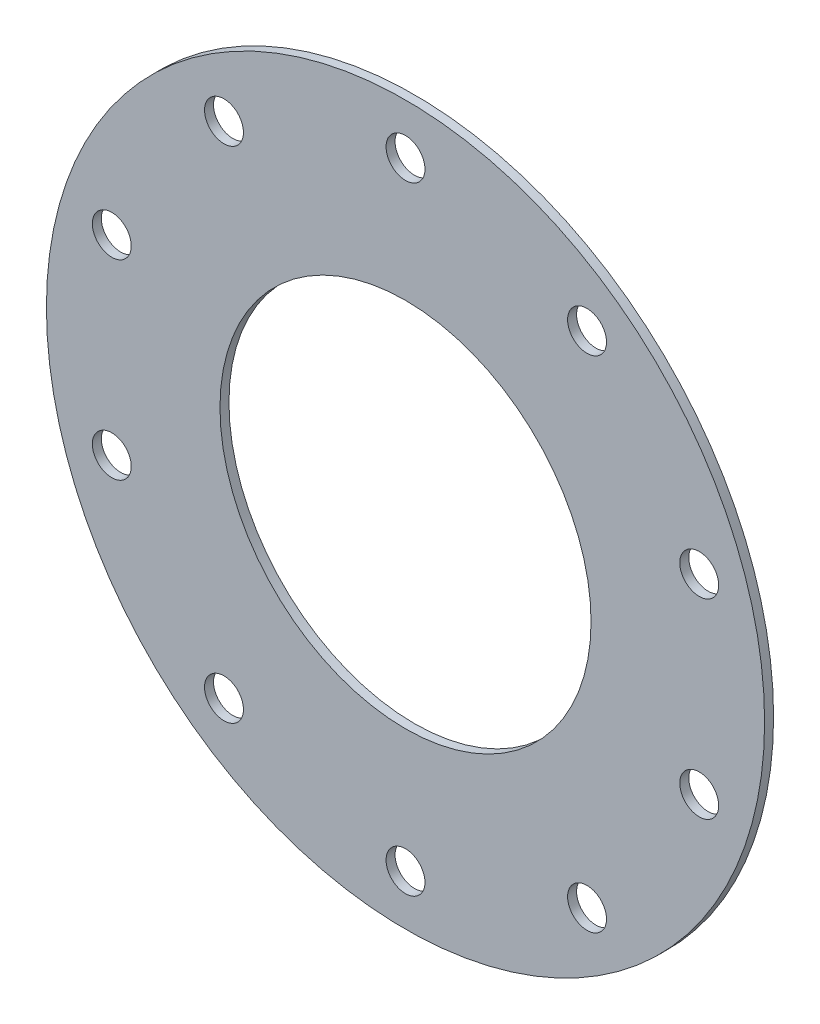
SolidWorks part; units mm, degrees
ref_plane "Front Plane" through (0, 0, 0) normal (0, 0, 1) x (1, 0, 0)
ref_plane "Top Plane" through (0, 0, 0) normal (0, 1, 0) x (1, 0, 0)
ref_plane "Right Plane" through (0, 0, 0) normal (1, 0, 0) x (0, 0, -1)
sketch "Sketch1" plane through (0, 0, 0) normal (0, 0, 1) x (1, 0, 0)
  circle A0 centre (0, 0) radius 60
  circle A1 centre (0, 0) radius 31
  circle A2 centre (0, 0) radius 51.6 construction
  circle A3 centre (0, 51.6) radius 3.25
  circle A4 centre (30.3297, 41.7453) radius 3.25
  circle A5 centre (49.0745, 15.9453) radius 3.25
  circle A6 centre (49.0745, -15.9453) radius 3.25
  circle A7 centre (30.3297, -41.7453) radius 3.25
  circle A8 centre (0, -51.6) radius 3.25
  circle A9 centre (-30.3297, -41.7453) radius 3.25
  circle A10 centre (-49.0745, -15.9453) radius 3.25
  circle A11 centre (-49.0745, 15.9453) radius 3.25
  circle A12 centre (-30.3297, 41.7453) radius 3.25
  point P24 (0, 0)
  dimension "D1" = 120
  dimension "D2" = 103.2
  dimension "D3" = 62
  dimension "D4" = 6.5
  dimension "D5" = 10
extrude "Boss-Extrude1" add sketch "Sketch1" along normal blind 1.5
